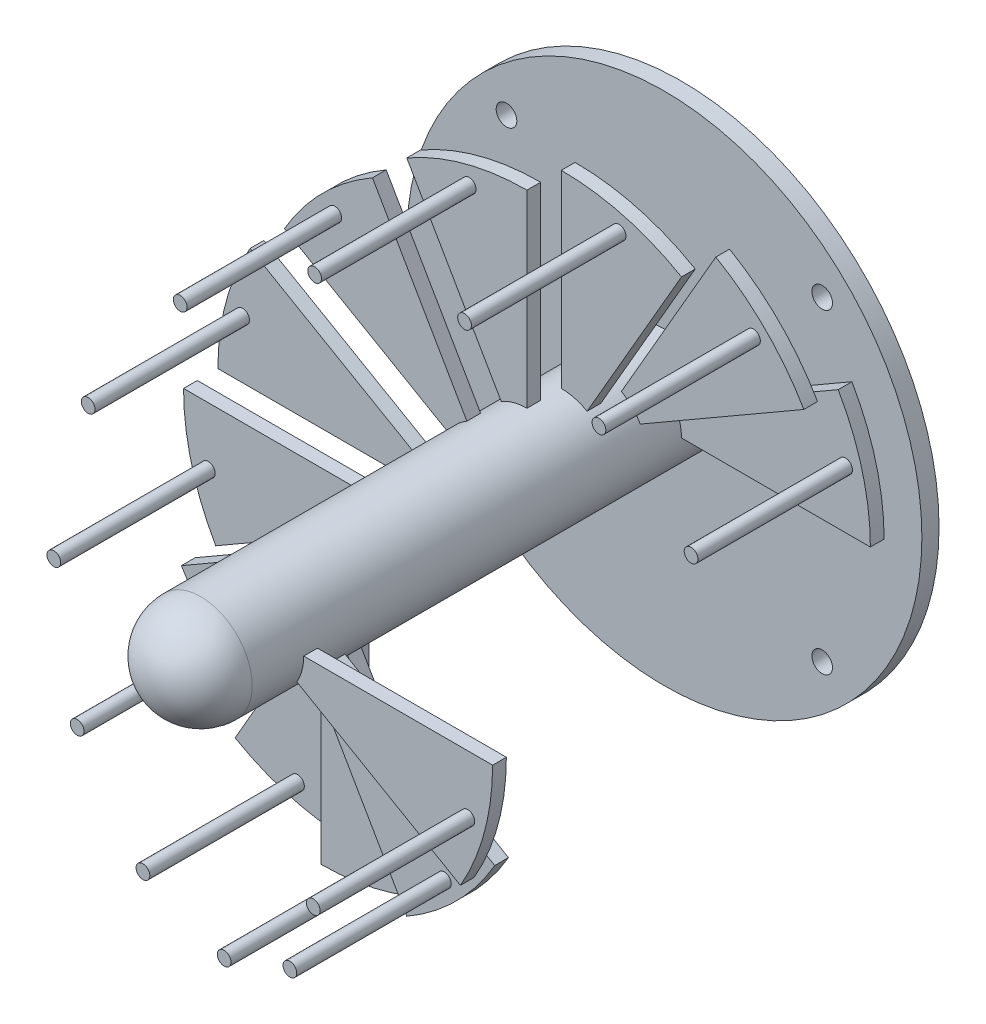
SolidWorks part; units mm, degrees
ref_plane "前视基准面" through (0, 0, 0) normal (0, 0, 1) x (1, 0, 0)
ref_plane "上视基准面" through (0, 0, 0) normal (0, 1, 0) x (1, 0, 0)
ref_plane "右视基准面" through (0, 0, 0) normal (1, 0, 0) x (0, 0, -1)
sketch "草图1" plane through (0, 0, 0) normal (0, 0, 1) x (1, 0, 0)
  circle A0 centre (0, 0) radius 150
extrude "凸台-拉伸1" add sketch "草图1" along normal blind 10
sketch "草图2" plane through (0, 0, 0) normal (0, 0, 1) x (1, 0, 0)
  circle A0 centre (0, 0) radius 30
extrude "凸台-拉伸2" add sketch "草图2" along normal blind 280
sketch "草图3" plane through (0, 0, 0) normal (0, 1, 0) x (1, 0, 0)
  line L0 (0, -270) -> (0, -310) construction
  line L1 (0, -280) -> (30, -280)
  line L2 (0, -310) -> (0, -280)
  arc A0 (30, -280) -> (0, -310) centre (0, -280) cw
revolve "旋转1" add sketch "草图3" angle 360 about L0
ref_plane "基准面1" through (0, 0, 22) normal (0, 0, 1) x (1, 0, 0)
sketch "草图4" plane through (0, 0, 22) normal (0, 0, 1) x (1, 0, 0)
  line L0 (121.2436, 70) -> (17.3205, 10)
  line L1 (20, 0) -> (140, 0)
  arc A0 (140, 0) -> (121.2436, 70) centre (0, 0) ccw
  arc A1 (17.3205, 10) -> (20, 0) centre (0, 0) cw
extrude "凸台-拉伸3" add sketch "草图4" along normal blind 8
ref_plane "基准面2" through (0, 0, 42) normal (0, 0, 1) x (1, 0, 0)
sketch "草图5" plane through (0, 0, 42) normal (0, 0, 1) x (1, 0, 0)
  line L0 (70, 121.2436) -> (10, 17.3205)
  line L1 (17.3205, 10) -> (121.2436, 70)
  arc A0 (121.2436, 70) -> (70, 121.2436) centre (0, 0) ccw
  arc A1 (10, 17.3205) -> (17.3205, 10) centre (0, 0) cw
extrude "凸台-拉伸4" add sketch "草图5" along normal blind 8
ref_plane "基准面3" through (0, 0, 62) normal (0, 0, 1) x (1, 0, 0)
sketch "草图6" plane through (0, 0, 62) normal (0, 0, 1) x (1, 0, 0)
  line L0 (0, 140) -> (0, 20)
  line L1 (10, 17.3205) -> (70, 121.2436)
  arc A0 (70, 121.2436) -> (0, 140) centre (0, 0) ccw
  arc A1 (0, 20) -> (10, 17.3205) centre (0, 0) cw
extrude "凸台-拉伸5" add sketch "草图6" along normal blind 8
ref_plane "基准面4" through (0, 0, 82) normal (0, 0, 1) x (1, 0, 0)
sketch "草图7" plane through (0, 0, 82) normal (0, 0, 1) x (1, 0, 0)
  line L0 (-70, 121.2436) -> (-10, 17.3205)
  line L1 (0, 20) -> (0, 140)
  arc A0 (0, 140) -> (-70, 121.2436) centre (0, 0) ccw
  arc A1 (-10, 17.3205) -> (0, 20) centre (0, 0) cw
extrude "凸台-拉伸6" add sketch "草图7" along normal blind 8
ref_plane "基准面5" through (0, 0, 102) normal (0, 0, 1) x (1, 0, 0)
sketch "草图8" plane through (0, 0, 102) normal (0, 0, 1) x (1, 0, 0)
  line L0 (-121.2436, 70) -> (-17.3205, 10)
  line L1 (-10, 17.3205) -> (-70, 121.2436)
  arc A0 (-70, 121.2436) -> (-121.2436, 70) centre (0, 0) ccw
  arc A1 (-17.3205, 10) -> (-10, 17.3205) centre (0, 0) cw
extrude "凸台-拉伸7" add sketch "草图8" along normal blind 8
ref_plane "基准面6" through (0, 0, 122) normal (0, 0, 1) x (1, 0, 0)
sketch "草图9" plane through (0, 0, 122) normal (0, 0, 1) x (1, 0, 0)
  line L0 (-140, 0) -> (-20, 0)
  line L1 (-17.3205, 10) -> (-121.2436, 70)
  arc A0 (-121.2436, 70) -> (-140, 0) centre (0, 0) ccw
  arc A1 (-20, 0) -> (-17.3205, 10) centre (0, 0) cw
extrude "凸台-拉伸8" add sketch "草图9" along normal blind 8
ref_plane "基准面7" through (0, 0, 142) normal (0, 0, 1) x (1, 0, 0)
sketch "草图10" plane through (0, 0, 142) normal (0, 0, 1) x (1, 0, 0)
  line L0 (-121.2436, -70) -> (-17.3205, -10)
  line L1 (-20, 0) -> (-140, 0)
  arc A0 (-140, 0) -> (-121.2436, -70) centre (0, 0) ccw
  arc A1 (-17.3205, -10) -> (-20, 0) centre (0, 0) cw
extrude "凸台-拉伸9" add sketch "草图10" along normal blind 8
ref_plane "基准面8" through (0, 0, 162) normal (0, 0, 1) x (1, 0, 0)
sketch "草图11" plane through (0, 0, 162) normal (0, 0, 1) x (1, 0, 0)
  line L0 (-70, -121.2436) -> (-10, -17.3205)
  line L1 (-17.3205, -10) -> (-121.2436, -70)
  arc A0 (-121.2436, -70) -> (-70, -121.2436) centre (0, 0) ccw
  arc A1 (-10, -17.3205) -> (-17.3205, -10) centre (0, 0) cw
extrude "凸台-拉伸10" add sketch "草图11" along normal blind 8
ref_plane "基准面9" through (0, 0, 182) normal (0, 0, 1) x (1, 0, 0)
sketch "草图12" plane through (0, 0, 182) normal (0, 0, 1) x (1, 0, 0)
  line L0 (0, -140) -> (0, -20)
  line L1 (-10, -17.3205) -> (-70, -121.2436)
  arc A0 (-70, -121.2436) -> (0, -140) centre (0, 0) ccw
  arc A1 (0, -20) -> (-10, -17.3205) centre (0, 0) cw
extrude "凸台-拉伸11" add sketch "草图12" along normal blind 8
ref_plane "基准面10" through (0, 0, 202) normal (0, 0, 1) x (1, 0, 0)
sketch "草图13" plane through (0, 0, 202) normal (0, 0, 1) x (1, 0, 0)
  line L0 (70, -121.2436) -> (10, -17.3205)
  line L1 (0, -20) -> (0, -140)
  arc A0 (0, -140) -> (70, -121.2436) centre (0, 0) ccw
  arc A1 (10, -17.3205) -> (0, -20) centre (0, 0) cw
extrude "凸台-拉伸12" add sketch "草图13" along normal blind 8
ref_plane "基准面11" through (0, 0, 222) normal (0, 0, 1) x (1, 0, 0)
sketch "草图14" plane through (0, 0, 222) normal (0, 0, 1) x (1, 0, 0)
  line L0 (121.2436, -70) -> (17.3205, -10)
  line L1 (10, -17.3205) -> (70, -121.2436)
  arc A0 (70, -121.2436) -> (121.2436, -70) centre (0, 0) ccw
  arc A1 (17.3205, -10) -> (10, -17.3205) centre (0, 0) cw
extrude "凸台-拉伸13" add sketch "草图14" along normal blind 8
ref_plane "基准面12" through (0, 0, 242) normal (0, 0, 1) x (1, 0, 0)
sketch "草图15" plane through (0, 0, 242) normal (0, 0, 1) x (1, 0, 0)
  line L0 (140, 0) -> (20, 0)
  line L1 (17.3205, -10) -> (121.2436, -70)
  arc A0 (121.2436, -70) -> (140, 0) centre (0, 0) ccw
  arc A1 (20, 0) -> (17.3205, -10) centre (0, 0) cw
extrude "凸台-拉伸14" add sketch "草图15" along normal blind 8
ref_plane "基准面13" through (0, 0, 28) normal (0, 0, 1) x (1, 0, 0)
sketch "草图16" plane through (0, 0, 28) normal (0, 0, 1) x (1, 0, 0)
  circle A0 centre (125.566, 33.648) radius 4
extrude "凸台-拉伸15" add sketch "草图16" along normal blind 92
ref_plane "基准面14" through (0, 0, 48) normal (0, 0, 1) x (1, 0, 0)
sketch "草图17" plane through (0, 0, 48) normal (0, 0, 1) x (1, 0, 0)
  circle A0 centre (91.925, 91.925) radius 4
extrude "凸台-拉伸16" add sketch "草图17" along normal blind 92
ref_plane "基准面15" through (0, 0, 68) normal (0, 0, 1) x (1, 0, 0)
sketch "草图18" plane through (0, 0, 68) normal (0, 0, 1) x (1, 0, 0)
  circle A0 centre (33.648, 125.566) radius 4
extrude "凸台-拉伸17" add sketch "草图18" along normal blind 92
ref_plane "基准面16" through (0, 0, 88) normal (0, 0, 1) x (1, 0, 0)
sketch "草图19" plane through (0, 0, 88) normal (0, 0, 1) x (1, 0, 0)
  circle A0 centre (-33.648, 125.566) radius 4
extrude "凸台-拉伸18" add sketch "草图19" along normal blind 92
ref_plane "基准面17" through (0, 0, 108) normal (0, 0, 1) x (1, 0, 0)
sketch "草图20" plane through (0, 0, 108) normal (0, 0, 1) x (1, 0, 0)
  circle A0 centre (-91.925, 91.925) radius 4
extrude "凸台-拉伸19" add sketch "草图20" along normal blind 92
ref_plane "基准面18" through (0, 0, 128) normal (0, 0, 1) x (1, 0, 0)
sketch "草图21" plane through (0, 0, 128) normal (0, 0, 1) x (1, 0, 0)
  circle A0 centre (-125.566, 33.648) radius 4
extrude "凸台-拉伸20" add sketch "草图21" along normal blind 92
ref_plane "基准面19" through (0, 0, 148) normal (0, 0, 1) x (1, 0, 0)
sketch "草图22" plane through (0, 0, 148) normal (0, 0, 1) x (1, 0, 0)
  circle A0 centre (-125.566, -33.648) radius 4
extrude "凸台-拉伸21" add sketch "草图22" along normal blind 92
ref_plane "基准面20" through (0, 0, 168) normal (0, 0, 1) x (1, 0, 0)
sketch "草图23" plane through (0, 0, 168) normal (0, 0, 1) x (1, 0, 0)
  circle A0 centre (-91.925, -91.925) radius 4
extrude "凸台-拉伸22" add sketch "草图23" along normal blind 92
ref_plane "基准面21" through (0, 0, 188) normal (0, 0, 1) x (1, 0, 0)
sketch "草图24" plane through (0, 0, 188) normal (0, 0, 1) x (1, 0, 0)
  circle A0 centre (-33.648, -125.566) radius 4
extrude "凸台-拉伸23" add sketch "草图24" along normal blind 92
ref_plane "基准面22" through (0, 0, 208) normal (0, 0, 1) x (1, 0, 0)
sketch "草图25" plane through (0, 0, 208) normal (0, 0, 1) x (1, 0, 0)
  circle A0 centre (33.648, -125.566) radius 4
extrude "凸台-拉伸24" add sketch "草图25" along normal blind 92
ref_plane "基准面23" through (0, 0, 228) normal (0, 0, 1) x (1, 0, 0)
sketch "草图26" plane through (0, 0, 228) normal (0, 0, 1) x (1, 0, 0)
  circle A0 centre (91.925, -91.925) radius 4
extrude "凸台-拉伸25" add sketch "草图26" along normal blind 92
ref_plane "基准面24" through (0, 0, 248) normal (0, 0, 1) x (1, 0, 0)
sketch "草图27" plane through (0, 0, 248) normal (0, 0, 1) x (1, 0, 0)
  circle A0 centre (125.566, -33.648) radius 4
extrude "凸台-拉伸26" add sketch "草图27" along normal blind 92
sketch "草图28" plane through (0, 0, 0) normal (0, 0, 1) x (1, 0, 0)
  circle A0 centre (100, 0) radius 10
extrude "切除-拉伸1" cut sketch "草图28" along normal blind 10.5
sketch "草图29" plane through (0, 0, 0) normal (0, 0, 1) x (1, 0, 0)
  circle A0 centre (91.9239, 91.9239) radius 6
  circle A1 centre (-91.9239, 91.9239) radius 6
  circle A2 centre (-91.9239, -91.9239) radius 6
  circle A3 centre (91.9239, -91.9239) radius 6
extrude "切除-拉伸2" cut sketch "草图29" along normal blind 10.5
